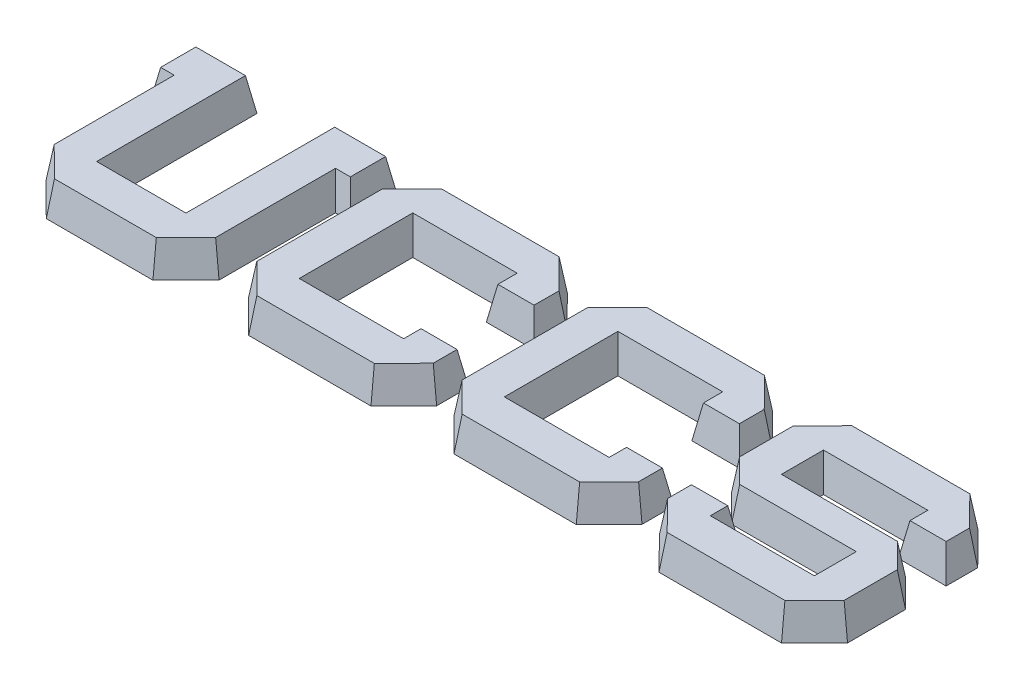
SolidWorks part; units mm, degrees
ref_plane "Front Plane" through (0, 0, 0) normal (0, 0, 1) x (1, 0, 0)
ref_plane "Top Plane" through (0, 0, 0) normal (0, 1, 0) x (1, 0, 0)
ref_plane "Right Plane" through (0, 0, 0) normal (1, 0, 0) x (0, 0, -1)
sketch "Sketch2" plane through (0, 0, 0) normal (0, 1, 0) x (1, 0, 0)
  line L0 (97.7282, 36.0482) -> (82.7685, 36.0415)
  line L1 (82.7685, 36.0415) -> (78.8102, 32.016)
  line L2 (78.8102, 32.016) -> (78.8102, 24.9193)
  line L3 (78.8102, 24.9193) -> (82.1301, 21.6061)
  line L4 (82.1301, 21.6061) -> (95.9204, 21.6128)
  line L5 (95.9204, 21.6128) -> (95.9204, 17.9166)
  line L6 (95.9204, 17.9166) -> (84.6502, 17.9166)
  line L7 (84.6502, 17.9166) -> (84.6502, 20.0402)
  line L8 (84.6502, 20.0402) -> (78.8169, 20.0402)
  line L9 (78.8169, 20.0402) -> (78.8169, 16.1424)
  line L10 (78.8169, 16.1424) -> (82.7753, 12.1169)
  line L11 (82.7753, 12.1169) -> (97.7147, 12.1169)
  line L12 (97.7147, 12.1169) -> (101.7335, 16.1424)
  line L13 (101.7335, 16.1424) -> (101.7335, 23.2123)
  line L14 (101.7335, 23.2123) -> (98.3263, 26.6195)
  line L15 (98.3263, 26.6195) -> (84.6099, 26.6195)
  line L16 (84.6099, 26.6195) -> (84.6099, 30.3359)
  line L17 (84.6099, 30.3359) -> (95.9137, 30.3359)
  line L18 (95.9137, 30.3359) -> (95.9137, 28.1585)
  line L19 (95.9137, 28.1585) -> (101.7335, 28.1585)
  line L20 (101.7335, 28.1585) -> (101.7335, 32.0093)
  line L21 (101.7335, 32.0093) -> (97.7282, 36.0482)
  line L22 (72.7081, 36.0348) -> (57.8022, 36.0348)
  line L23 (57.8022, 36.0348) -> (53.7901, 32.0093)
  line L24 (53.7901, 32.0093) -> (53.7834, 16.1289)
  line L25 (53.7834, 16.1289) -> (57.8022, 12.1101)
  line L26 (57.8022, 12.1101) -> (72.7081, 12.1101)
  line L27 (72.7081, 12.1101) -> (76.6933, 16.1357)
  line L28 (76.6933, 16.1357) -> (76.6933, 20.0335)
  line L29 (76.6933, 20.0335) -> (70.9138, 20.0335)
  line L30 (70.9138, 20.0335) -> (70.9138, 17.9099)
  line L31 (70.9138, 17.9099) -> (59.5563, 17.9099)
  line L32 (59.5563, 17.9099) -> (59.5563, 30.3359)
  line L33 (59.5563, 30.3359) -> (70.9138, 30.3359)
  line L34 (70.9138, 30.3359) -> (70.9138, 27.9905)
  line L35 (70.9138, 27.9905) -> (76.7067, 27.9905)
  line L36 (76.7067, 27.9905) -> (76.7067, 32.016)
  line L37 (76.7067, 32.016) -> (72.7081, 36.0348)
  line L38 (47.688, 36.0348) -> (32.7822, 36.0348)
  line L39 (32.7822, 36.0348) -> (28.7633, 32.0093)
  line L40 (28.7633, 32.0093) -> (28.7566, 16.1289)
  line L41 (28.7566, 16.1289) -> (32.7822, 12.1101)
  line L42 (32.7822, 12.1101) -> (47.688, 12.1101)
  line L43 (47.688, 12.1101) -> (51.6665, 16.1357)
  line L44 (51.6665, 16.1357) -> (51.6665, 20.0335)
  line L45 (51.6665, 20.0335) -> (45.8668, 20.0335)
  line L46 (45.8668, 20.0335) -> (45.8668, 17.9099)
  line L47 (45.8668, 17.9099) -> (34.5563, 17.9099)
  line L48 (34.5563, 17.9099) -> (34.5563, 30.3359)
  line L49 (34.5563, 30.3359) -> (45.8668, 30.3359)
  line L50 (45.8668, 30.3359) -> (45.8668, 27.9905)
  line L51 (45.8668, 27.9905) -> (51.6799, 27.9905)
  line L52 (51.6799, 27.9905) -> (51.6934, 32.016)
  line L53 (51.6934, 32.016) -> (47.688, 36.0348)
  line L54 (26.9488, 36.0415) -> (19.3413, 36.0415)
  line L55 (19.3413, 36.0415) -> (19.3413, 17.9099)
  line L56 (19.3413, 17.9099) -> (9.8656, 17.9099)
  line L57 (9.8656, 17.9099) -> (9.8656, 36.0415)
  line L58 (9.8656, 36.0415) -> (2.4193, 36.0415)
  line L59 (2.4193, 36.0415) -> (2.4193, 30.3359)
  line L60 (2.4193, 30.3359) -> (4.0726, 30.3359)
  line L61 (4.0726, 30.3359) -> (4.0726, 16.1222)
  line L62 (4.0726, 16.1222) -> (8.125, 12.1034)
  line L63 (8.125, 12.1034) -> (21.1222, 12.1034)
  line L64 (21.1222, 12.1034) -> (25.141, 16.1424)
  line L65 (25.141, 16.1424) -> (25.141, 30.3359)
  line L66 (25.141, 30.3359) -> (26.9488, 30.3359)
  line L67 (26.9488, 30.3359) -> (26.9488, 36.0415)
extrude "Boss-Extrude1" add sketch "Sketch2" along normal blind 4 draft 10 contours L38 L39 L40 L41 L42 L43 L44 L45 L46 L47 L48 L49 L50 L51 L52 L53
sketch "Sketch3" plane through (0, 0, 0) normal (0, -1, 0) x (1, 0, 0)
  circle A0 centre (90.7633, -33.1414) radius 1 construction
  circle A1 centre (90.7633, -15.0036) radius 1 construction
  circle A2 centre (65.7229, -15.0036) radius 1 construction
  circle A3 centre (65.7229, -33.1414) radius 1 construction
  circle A4 centre (40.1127, -33.1414) radius 1 construction
  circle A5 centre (40.1127, -15.0036) radius 1 construction
  circle A6 centre (21.9626, -21.9901) radius 1 construction
  circle A7 centre (6.9626, -21.9901) radius 1 construction
  circle A8 centre (90.7633, -33.1414) radius 1 construction
  circle A9 centre (90.7633, -15.0036) radius 1 construction
  circle A10 centre (65.7229, -15.0036) radius 1 construction
  circle A11 centre (65.7229, -33.1414) radius 1 construction
  circle A12 centre (40.1127, -33.1414) radius 1 construction
  circle A13 centre (40.1127, -15.0036) radius 1 construction
  circle A14 centre (21.9626, -21.9901) radius 1 construction
  circle A15 centre (6.9626, -21.9901) radius 1 construction
  circle A16 centre (90.7633, -33.1414) radius 1.127
  circle A17 centre (90.7633, -15.0036) radius 1.127
  circle A18 centre (65.7229, -15.0036) radius 1.127
  circle A19 centre (65.7229, -33.1414) radius 1.127
  circle A20 centre (40.1127, -33.1414) radius 1.127
  circle A21 centre (40.1127, -15.0036) radius 1.127
  circle A22 centre (21.9626, -21.9901) radius 1.127
  circle A23 centre (6.9626, -21.9901) radius 1.127
  dimension "D1" = 0.127
extrude "Cut-Extrude1" cut sketch "Sketch3" against normal blind 2.01
